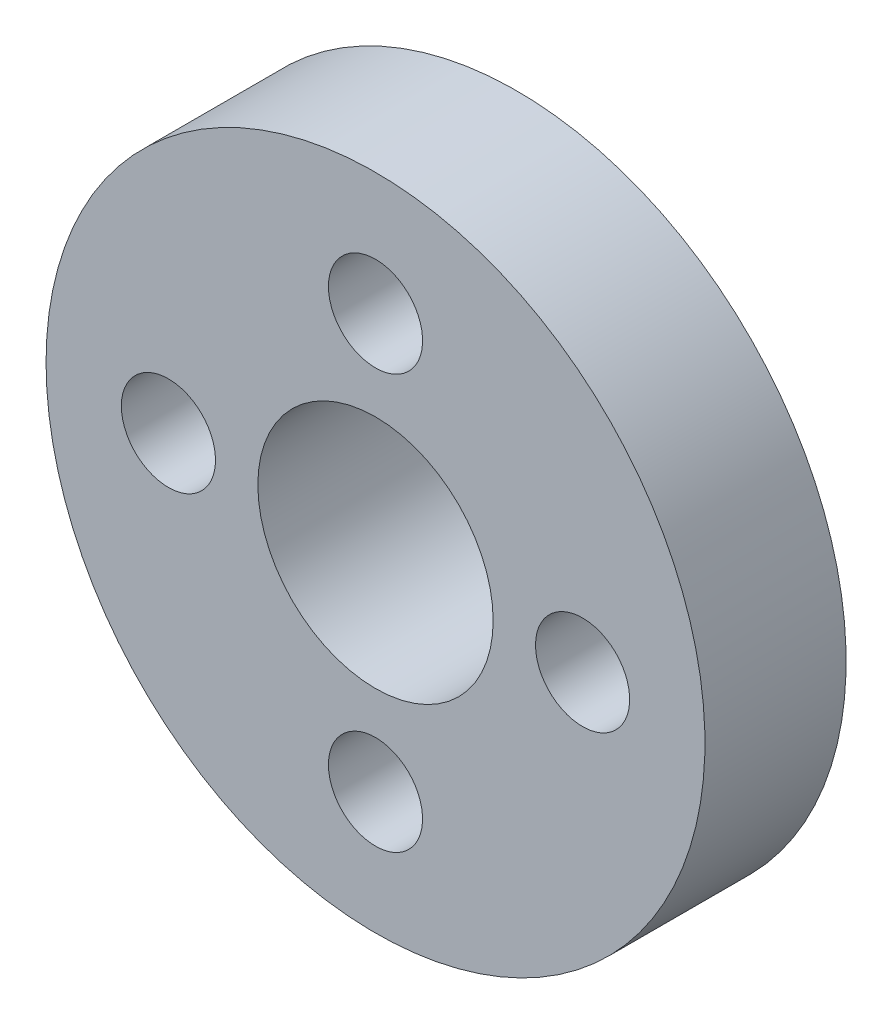
SolidWorks part; units mm, degrees
ref_plane "Front Plane" through (0, 0, 0) normal (0, 0, 1) x (1, 0, 0)
ref_plane "Top Plane" through (0, 0, 0) normal (0, 1, 0) x (1, 0, 0)
ref_plane "Right Plane" through (0, 0, 0) normal (1, 0, 0) x (0, 0, -1)
sketch "Sketch1" plane through (0, 0, 0) normal (0, 0, 1) x (1, 0, 0)
  line L0 (0, 11.176) -> (0, 0) construction
  line L5 (0, 0) -> (11.176, 0) construction
  line L6 (0, -11.176) -> (0, 0) construction
  line L7 (0, 0) -> (-11.176, 0) construction
  circle A0 centre (0, 0) radius 17.78
  circle A1 centre (-11.176, 0) radius 2.54
  circle A2 centre (0, -11.176) radius 2.54
  circle A3 centre (11.176, 0) radius 2.54
  circle A4 centre (0, 11.176) radius 2.54
  circle A5 centre (0, 0) radius 6.35
  dimension "D1" = 35.56
  dimension "D4" = 5.08
  dimension "D2" = 12.7
  dimension "D3" = 11.176
extrude "Boss-Extrude1" add sketch "Sketch1" along normal blind 7.62
sketch "Sketch2" plane through (0, 0, 0) normal (0, 0, -1) x (-1, 0, 0)
  line L1 (-8.255, -8.255) -> (8.255, -8.255)
  line L2 (-8.255, -8.255) -> (-8.255, 8.255)
  line L3 (-8.255, 8.255) -> (8.255, 8.255)
  line L4 (8.255, -8.255) -> (8.255, 8.255)
  line L5 (-8.255, -8.255) -> (8.255, 8.255) construction
  line L6 (-8.255, 8.255) -> (8.255, -8.255) construction
  circle A0 centre (0, 0) radius 6.35 construction
  circle A1 centre (0, 0) radius 6.35
  point P0 (0, 0)
  dimension "D1" = 16.51
extrude "Boss-Extrude2" add sketch "Sketch2" along normal blind 3.175
